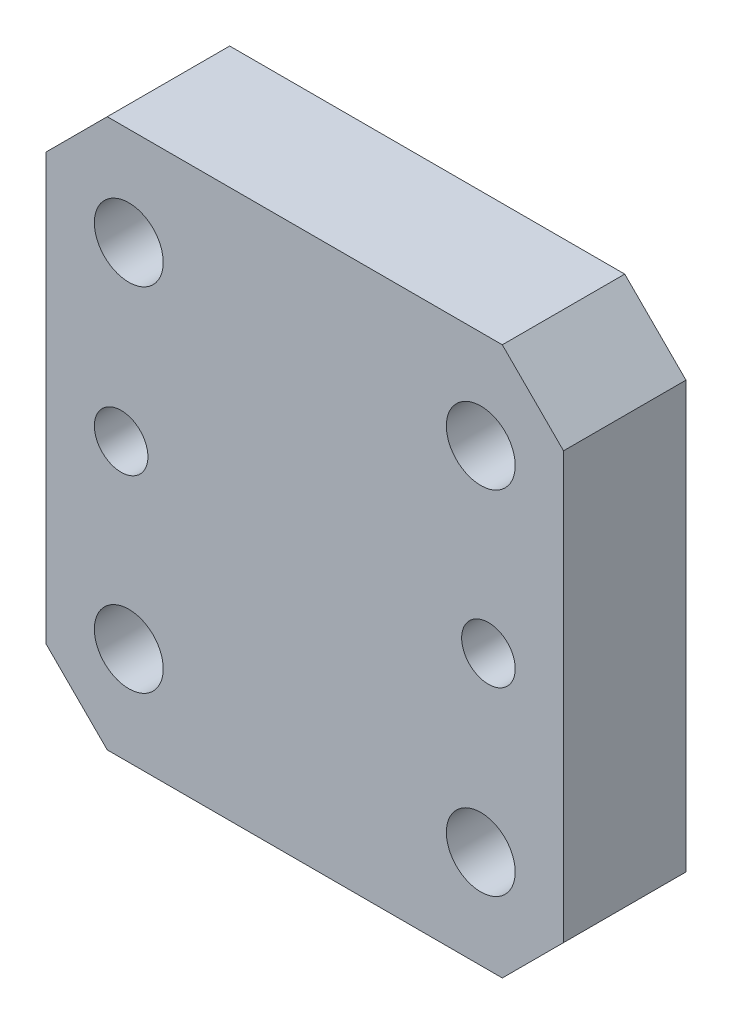
SolidWorks part; units mm, degrees
ref_plane "Front Plane" through (0, 0, 0) normal (0, 0, 1) x (1, 0, 0)
ref_plane "Top Plane" through (0, 0, 0) normal (0, 1, 0) x (1, 0, 0)
ref_plane "Right Plane" through (0, 0, 0) normal (1, 0, 0) x (0, 0, -1)
sketch "Sketch1" plane through (0, 0, 0) normal (0, 0, 1) x (1, 0, 0)
  line L1 (16.9073, 17.9163) -> (-16.9073, 17.9163)
  line L2 (16.9073, 17.9163) -> (16.9073, -17.9163)
  line L3 (16.9073, -17.9163) -> (-16.9073, -17.9163)
  line L4 (-16.9073, 17.9163) -> (-16.9073, -17.9163)
  line L5 (16.9073, 17.9163) -> (-16.9073, -17.9163) construction
  line L6 (16.9073, -17.9163) -> (-16.9073, 17.9163) construction
  point P0 (0, 0)
  point P6 (14.5, -22.4447)
  point P7 (20.6625, -25.3775)
  point P8 (-19.0366, -17.8135)
  point P9 (-17.5284, -18.1273)
  point P10 (-16.9073, -17.9163)
extrude "Boss-Extrude1" add sketch "Sketch1" along normal blind 8
sketch "Sketch2" plane through (0, 0, 8) normal (0, 0, 1) x (1, 0, 0)
  line L0 (-12, 0) -> (12, 0) construction
  circle A0 centre (-12, 0) radius 1.75
  circle A1 centre (12, 0) radius 1.75
  dimension "D2" = 3.5
  dimension "D1" = 24
extrude "Cut-Extrude1" cut sketch "Sketch2" against normal blind 8
sketch "Sketch3" plane through (0, 0, 0) normal (0, 0, -1) x (-1, 0, 0)
  circle A0 centre (11.5, -11.5) radius 2.25
  circle A1 centre (-11.5, -11.5) radius 2.25
  circle A2 centre (-11.5, 11.5) radius 2.25
  circle A3 centre (11.5, 11.5) radius 2.25
  dimension "D3" = 4.5
  dimension "D1" = 11.5
  dimension "D2" = 11.5
  dimension "D4" = 2
  dimension "D5" = 2
extrude "Cut-Extrude2" cut sketch "Sketch3" against normal blind 10
chamfer "Chamfer1" distance 4 angle 45 4 edges at (16.9073, 17.9163, 4) (16.9073, -17.9163, 4) (-16.9073, -17.9163, 4) (-16.9073, 17.9163, 4)
sketch "Sketch4" plane through (0, 0, 0) normal (0, 0, -1) x (-1, 0, 0)
  line L1 (-12, -3.5507) -> (-8.925, -1.7754)
  line L2 (-8.925, -1.7754) -> (-8.925, 1.7754)
  line L3 (-8.925, 1.7754) -> (-12, 3.5507)
  line L4 (-12, 3.5507) -> (-15.075, 1.7754)
  line L5 (-15.075, 1.7754) -> (-15.075, -1.7754)
  line L6 (-15.075, -1.7754) -> (-12, -3.5507)
  line L7 (12, -3.5507) -> (15.075, -1.7754)
  line L8 (15.075, -1.7754) -> (15.075, 1.7754)
  line L9 (15.075, 1.7754) -> (12, 3.5507)
  line L10 (12, 3.5507) -> (8.925, 1.7754)
  line L11 (8.925, 1.7754) -> (8.925, -1.7754)
  line L12 (8.925, -1.7754) -> (12, -3.5507)
  circle A0 centre (-12, 0) radius 3.075 construction
  circle A1 centre (12, 0) radius 3.075 construction
  dimension "D1" = 6.15
extrude "Cut-Extrude3" cut sketch "Sketch4" against normal blind 3
